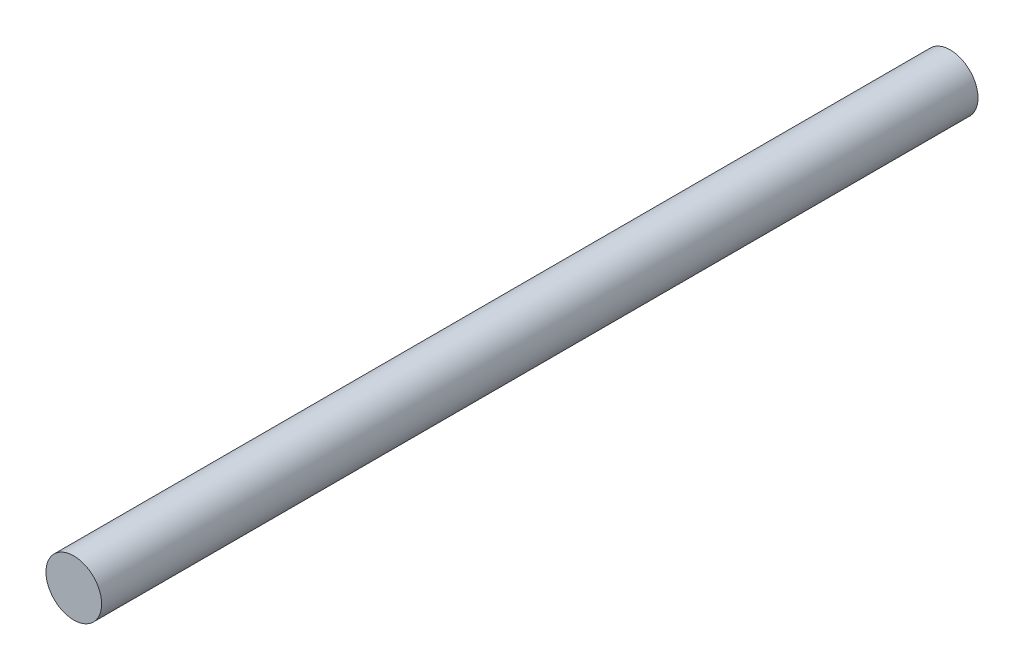
SolidWorks part; units mm, degrees
material "AISI 4340 Steel, normalized"
ref_plane "Front Plane" through (0, 0, 0) normal (0, 0, 1) x (1, 0, 0)
ref_plane "Top Plane" through (0, 0, 0) normal (0, 1, 0) x (1, 0, 0)
ref_plane "Right Plane" through (0, 0, 0) normal (1, 0, 0) x (0, 0, -1)
sketch "Sketch1" plane through (0, 0, 0) normal (0, 0, 1) x (1, 0, 0)
  circle A0 centre (0, 0) radius 4
extrude "Guide_Shaft" add sketch "Sketch1" along normal blind 126
